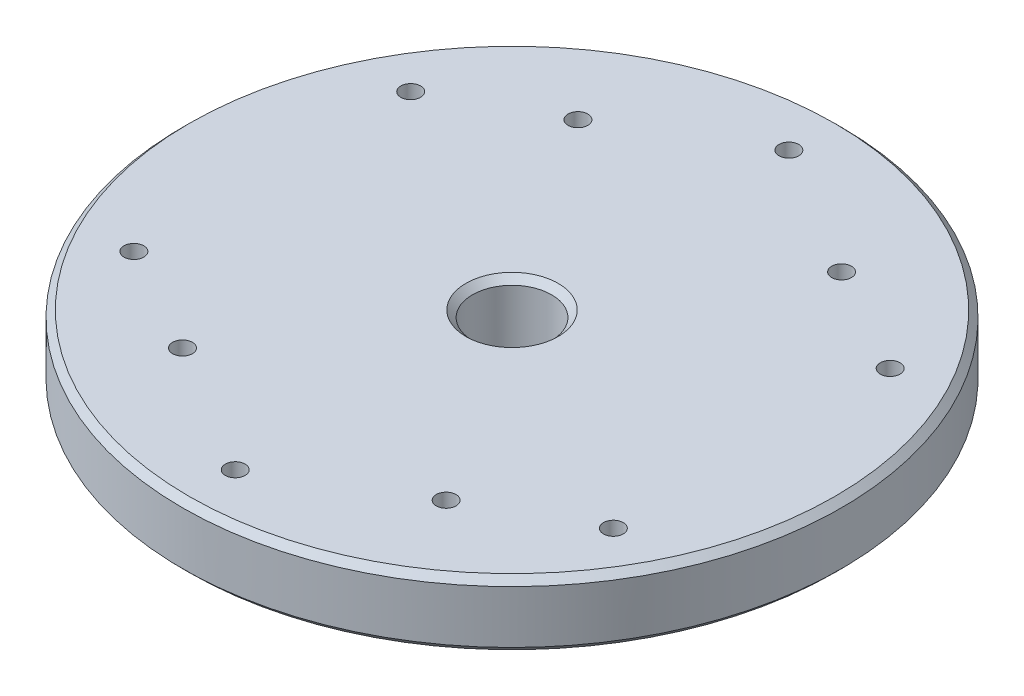
SolidWorks part; units mm, degrees
ref_plane "Front Plane" through (0, 0, 0) normal (0, 0, 1) x (1, 0, 0)
ref_plane "Top Plane" through (0, 0, 0) normal (0, 1, 0) x (1, 0, 0)
ref_plane "Right Plane" through (0, 0, 0) normal (1, 0, 0) x (0, 0, -1)
sketch "Sketch1" plane through (0, 0, 0) normal (0, 0, 1) x (1, 0, 0)
  line L0 (0, 0) -> (0, 14.5) construction
  line L2 (1.6, 0) -> (2, 0)
  line L6 (6.4, 6.2839) -> (6.4, 0) construction
  line L7 (6.4, 0) -> (2, 0) construction
  line L8 (6.4, 5.5) -> (5.9, 5.5) construction
  line L9 (1.6, 0) -> (1.6, 3.8)
  line L12 (3, 5.2) -> (3, 14.5)
  line L14 (6.5513, 9.5) -> (25, 9.5)
  line L15 (25, 9.5) -> (25, 14.5)
  line L16 (25, 14.5) -> (3, 14.5)
  line L17 (1.6, 3.8) -> (3, 5.2)
  line L20 (6.5513, 6.5) -> (6.5513, 9.5)
  line L21 (2, 0) -> (6.5513, 6.5)
  dimension "D1" = 1.6
  dimension "D2" = 5.9
  dimension "D3" = 35
  dimension "D4" = 4
  dimension "D5" = 0.5
  dimension "D6" = 5.5
  dimension "D7" = 3
  dimension "D8" = 45
  dimension "D9" = 5
  dimension "D10" = 25
  dimension "D11" = 3.8
  dimension "D12" = 3
  dimension "D13" = 2
revolve "Revolve1" add sketch "Sketch1" angle 360 about L0
ref_plane "Plane1" through (0, 0, 6) normal (0, 0, 1) x (1, 0, 0)
sketch "Sketch3" plane through (0, 0, 6) normal (0, 0, 1) x (1, 0, 0)
  line L1 (0.5, 0) -> (-0.5, 0)
  line L2 (0.5, 0) -> (0.5, 6.5)
  line L3 (0.5, 6.5) -> (-0.5, 6.5)
  line L4 (-0.5, 0) -> (-0.5, 6.5)
  line L5 (0, 6.5) -> (0, 0) construction
  line L6 (0.5, 3.25) -> (-0.5, 3.25) construction
  line L9 (6.5513, 6.5) -> (-6.5513, 6.5) construction
  point P380 (0, 3.25)
  dimension "D1" = 1
extrude "Boss-Extrude2" add sketch "Sketch3" against normal up to next
pattern_circular "CirPattern1" count 6 over 360 about axis through (0, 0, 0) along (0, 1, 0) of "Boss-Extrude2"
sketch "Sketch5" plane through (0, 14.5, 0) normal (0, 1, 0) x (1, 0, 0)
  line L0 (0, 0) -> (0, 21) construction
  circle A0 centre (0, 21) radius 0.75
  dimension "D1" = 1.5
  dimension "D2" = 21
extrude "Cut-Extrude1" cut sketch "Sketch5" against normal through all
pattern_circular "CirPattern2" count 6 over 360 about axis through (0, 0, 0) along (0, 1, 0) of "Cut-Extrude1"
sketch "Sketch6" plane through (0, 14.5, 0) normal (0, 1, 0) x (1, 0, 0)
  line L1 (-10, 15) -> (10, 15) construction
  line L2 (-10, 15) -> (-10, -15) construction
  line L3 (-10, -15) -> (10, -15) construction
  line L4 (10, 15) -> (10, -15) construction
  line L5 (0, -15) -> (0, 15) construction
  line L6 (-10, 0) -> (10, 0) construction
  circle A0 centre (-10, 15) radius 0.75
  circle A1 centre (10, 15) radius 0.75
  circle A2 centre (-10, -15) radius 0.75
  circle A3 centre (10, -15) radius 0.75
  point P124 (0, 0)
  dimension "D3" = 1.5
  dimension "D4" = 1.5
  dimension "D5" = 1.5
  dimension "D6" = 1.5
  dimension "D1" = 30
  dimension "D2" = 20
extrude "Cut-Extrude2" cut sketch "Sketch6" against normal through all
chamfer "Chamfer1" distance 0.5 angle 45 3 edges at (0, 14.5, -3) (0, 14.5, -25) (0, 9.5, -25)
equation "\"D4@Sketch6\"=\"D3@Sketch6\""
equation "\"D5@Sketch6\"=\"D3@Sketch6\""
equation "\"D6@Sketch6\"=\"D3@Sketch6\""
